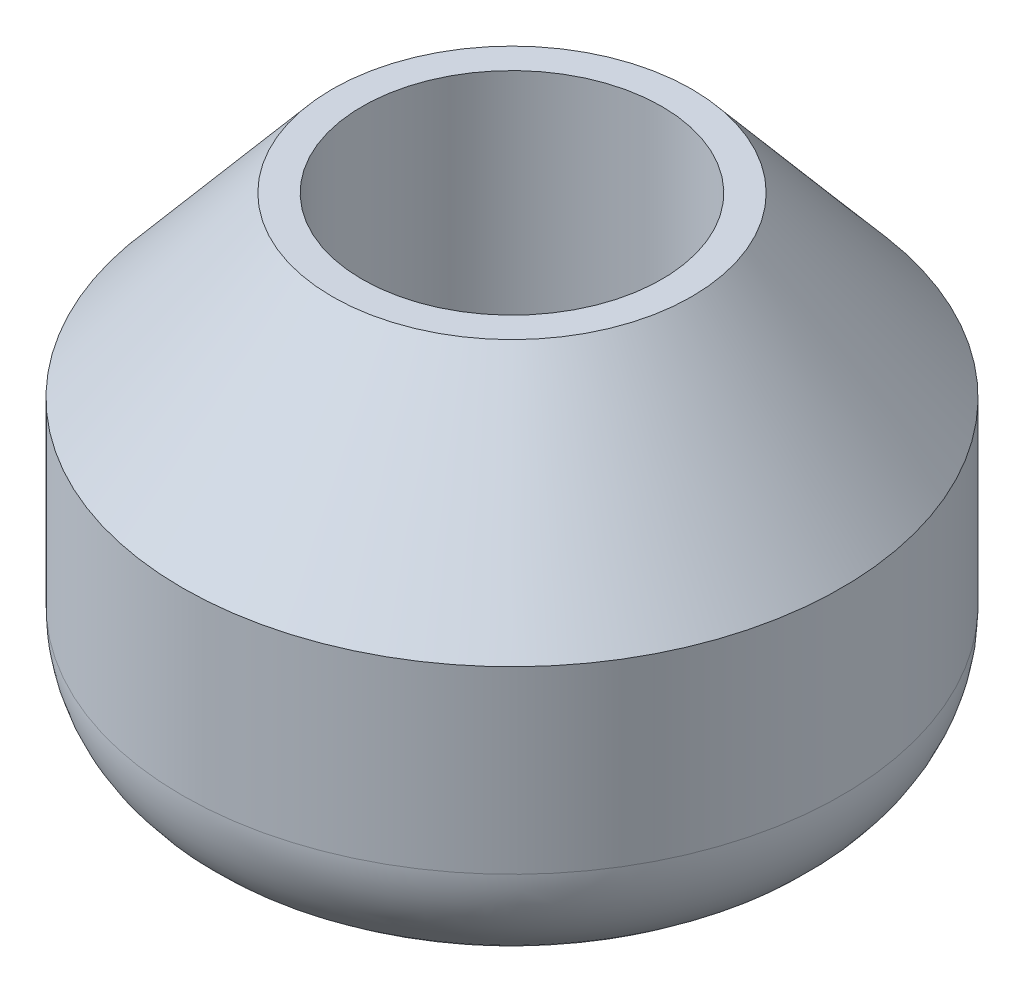
SolidWorks part; units mm, degrees
ref_plane "Piano frontale" through (0, 0, 0) normal (0, 0, 1) x (1, 0, 0)
ref_plane "Piano superiore" through (0, 0, 0) normal (0, 1, 0) x (1, 0, 0)
ref_plane "Piano destro" through (0, 0, 0) normal (1, 0, 0) x (0, 0, -1)
sketch "Schizzo1" plane through (0, 0, 0) normal (0, 0, 1) x (1, 0, 0)
  line L0 (0, 0) -> (0, 21.101) construction
  line L1 (5, 0) -> (5, 15.92)
  line L2 (5, 15.92) -> (6, 15.92)
  line L3 (11, 10) -> (11, 4)
  line L4 (7, 0) -> (5, 0)
  line L5 (6, 15.92) -> (11, 10)
  arc A0 (11, 4) -> (7, 0) centre (7, 4) cw
  dimension "D5" = 4
  dimension "D1" = 15.92
  dimension "D2" = 10
  dimension "D3" = 22
  dimension "D4" = 10
  dimension "D6" = 1
revolve "Rivoluzione1" add sketch "Schizzo1" angle 360 about L0
